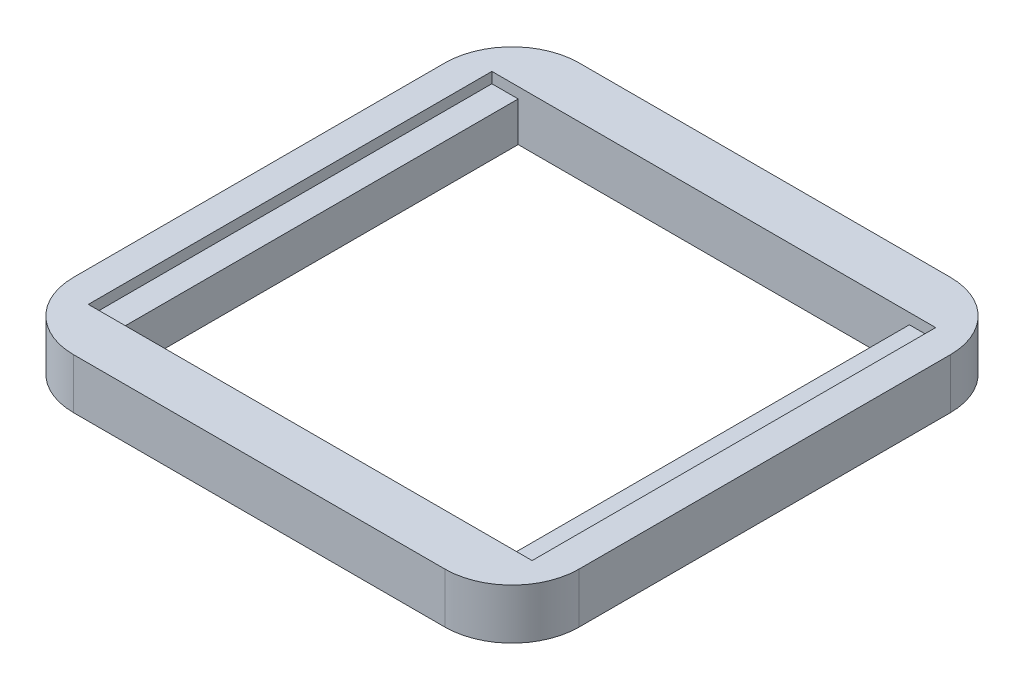
SolidWorks part; units mm, degrees
ref_plane "Front Plane" through (0, 0, 0) normal (0, 0, 1) x (1, 0, 0)
ref_plane "Top Plane" through (0, 0, 0) normal (0, 1, 0) x (1, 0, 0)
ref_plane "Right Plane" through (0, 0, 0) normal (1, 0, 0) x (0, 0, -1)
sketch "Sketch1" plane through (0, 0, 0) normal (0, 1, 0) x (1, 0, 0)
  line L1 (-37.7, -37.7) -> (37.7, -37.7)
  line L2 (-37.7, -37.7) -> (-37.7, 37.7)
  line L3 (-37.7, 37.7) -> (37.7, 37.7)
  line L4 (37.7, -37.7) -> (37.7, 37.7)
  line L5 (-37.7, -37.7) -> (37.7, 37.7) construction
  line L6 (-37.7, 37.7) -> (37.7, -37.7) construction
  point P0 (0, 0)
  dimension "D1" = 75.4
  dimension "D2" = 75.4
extrude "Base" add sketch "Sketch1" along normal blind 7.5
sketch "Sketch2" plane through (0, 7.5, 0) normal (0, 1, 0) x (1, 0, 0)
  line L0 (0, -4.125) -> (0, 4.125) construction
  line L1 (-33.1, -30.1) -> (33.1, -30.1)
  line L2 (-33.1, -30.1) -> (-33.1, 30.1)
  line L3 (-33.1, 30.1) -> (33.1, 30.1)
  line L4 (33.1, -30.1) -> (33.1, 30.1)
  line L5 (-33.1, -30.1) -> (33.1, 30.1) construction
  line L6 (-33.1, 30.1) -> (33.1, -30.1) construction
  line L7 (0, -4.125) -> (0, 4.125) construction
  point P1 (0, 0)
  dimension "D1" = 66.2
  dimension "D2" = 60.2
extrude "Slot" cut sketch "Sketch2" against normal blind 1.6
sketch "Sketch3" plane through (0, 5.9, 0) normal (0, 1, 0) x (1, 0, 0)
  line L6 (-29.1789, -30.1) -> (29.1789, -30.1)
  line L7 (-29.1789, -30.1) -> (-29.1789, 30.1)
  line L8 (-29.1789, 30.1) -> (29.1789, 30.1)
  line L9 (29.1789, -30.1) -> (29.1789, 30.1)
  line L10 (-29.1789, -30.1) -> (29.1789, 30.1) construction
  line L11 (-29.1789, 30.1) -> (29.1789, -30.1) construction
  line L12 (-33.1, 30.1) -> (33.1, -30.1) construction
  line L13 (-33.1, -30.1) -> (33.1, 30.1) construction
  line L16 (-33.1, -30.1) -> (33.1, -30.1) construction
  line L17 (33.1, 30.1) -> (-33.1, 30.1) construction
  point P2 (0, 37.5)
  point P4 (0, 0)
  point P8 (0, 0)
extrude "Slot-Components" cut sketch "Sketch3" against normal up to surface (5.9 mm away) up to face at (0, 0, 0)
fillet "Fillet2" radius 10 4 edges at (-37.7, 3.75, -37.7) (37.7, 3.75, -37.7) (37.7, 3.75, 37.7) (-37.7, 3.75, 37.7)
